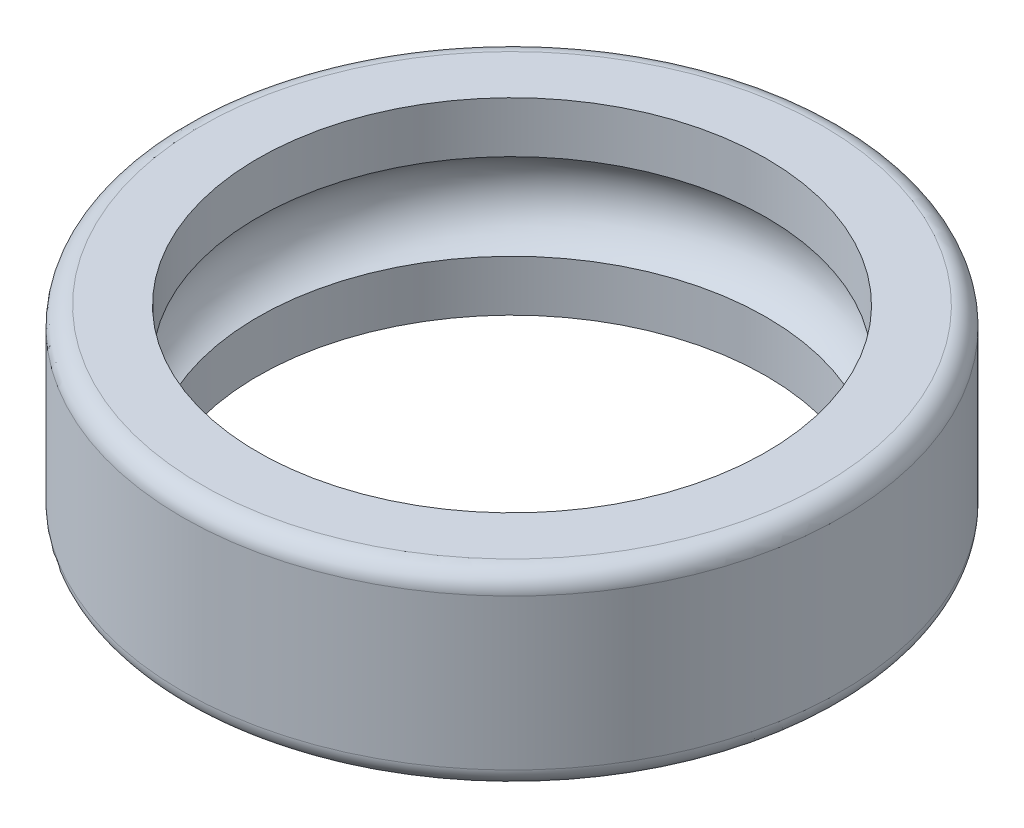
SolidWorks part; units mm, degrees
ref_plane "Front Plane" through (0, 0, 0) normal (1, 0, 0) x (0, 1, 0)
ref_plane "Top Plane" through (0, 0, 0) normal (0, 0, 1) x (0, 1, 0)
ref_plane "Right Plane" through (0, 0, 0) normal (0, 1, 0) x (-1, 0, 0)
sketch "Sketch1" plane through (0, 0, 0) normal (1, 0, 0) x (0, 1, 0)
  line L0 (-30.4353, 0) -> (32.496, 0) construction
  line L1 (0, 30.1975) -> (0, -27.1857) construction
  line L2 (-5, 12.5) -> (5, 12.5) construction
  line L3 (-4, 17.5) -> (4, 17.5)
  line L4 (-5, 16.5) -> (-5, 13.5)
  line L6 (5, 16.5) -> (5, 13.5)
  line L7 (-5, 13.5) -> (-2.2913, 13.5)
  line L11 (2.2913, 13.5) -> (5, 13.5)
  arc A1 (2.2913, 13.5) -> (-2.2913, 13.5) centre (0, 12.5) ccw
  arc A2 (4, 17.5) -> (5, 16.5) centre (4, 16.5) cw
  arc A3 (-4, 17.5) -> (-5, 16.5) centre (-4, 16.5) ccw
  point P5 (0, 0)
  point P6 (0, 0)
  point P8 (0, 0)
  point P17 (5, 17.5)
  point P22 (-5, 17.5)
  dimension "D4" = 2.5
  dimension "D6" = 1
  dimension "D1" = 10
  dimension "D2" = 5
  dimension "D3" = 17.5
  dimension "D5" = 1
revolve "Revolve1" add sketch "Sketch1" angle 360 about L0
